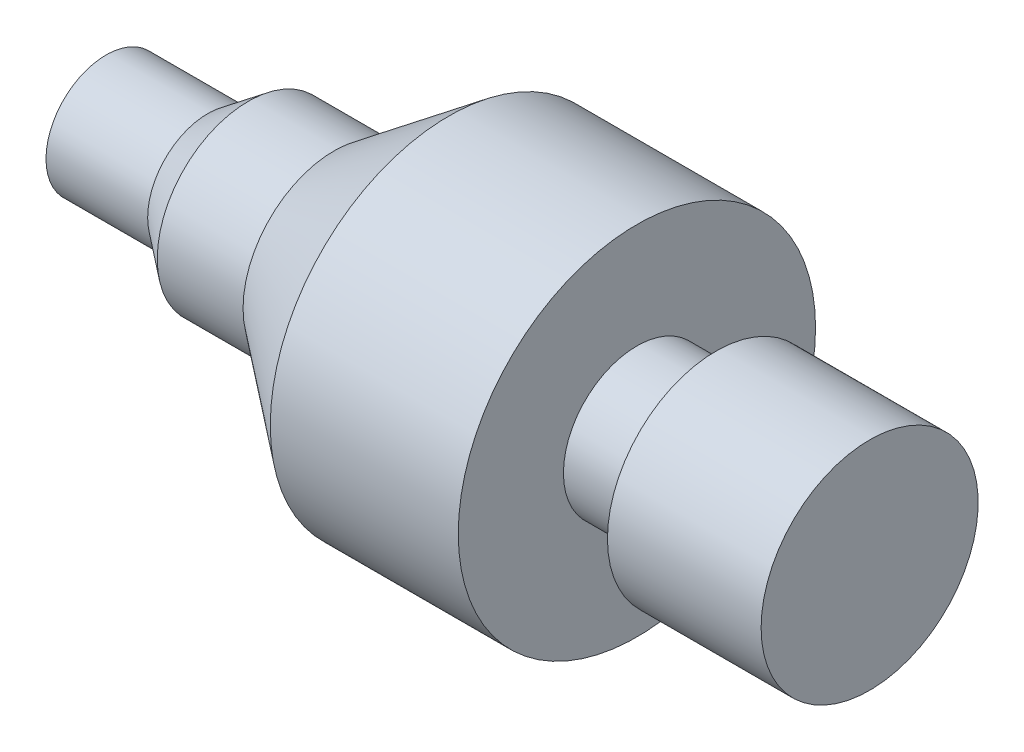
SolidWorks part; units mm, degrees
material "Nickel"
ref_plane "Front Plane" through (0, 0, 0) normal (0, 0, 1) x (1, 0, 0)
ref_plane "Top Plane" through (0, 0, 0) normal (0, 1, 0) x (1, 0, 0)
ref_plane "Right Plane" through (0, 0, 0) normal (1, 0, 0) x (0, 0, -1)
sketch "Sketch1" plane through (0, 0, 0) normal (0, 0, 1) x (1, 0, 0)
  circle A0 centre (-1.4989, 0) radius 34.7002
sketch "Sketch2" plane through (0, 0, 0) normal (0, 0, 1) x (1, 0, 0)
  line L0 (0, 0) -> (68.4973, 0) construction
  line L1 (68.4973, 0) -> (68.4973, 9.7366)
  line L2 (68.4973, 9.7366) -> (54.7122, 9.7366)
  line L3 (54.7122, 9.7366) -> (54.7122, 6.5914)
  line L4 (54.7122, 6.5914) -> (47.6189, 6.5914)
  line L5 (47.6189, 6.5914) -> (47.6189, 16.0269)
  line L6 (47.6189, 16.0269) -> (30.7556, 16.0269)
  line L7 (30.7556, 16.0269) -> (20.4502, 8.164)
  line L8 (20.4502, 8.164) -> (12.7546, 8.164)
  line L9 (12.7546, 8.164) -> (9.1192, 5.3902)
  line L10 (9.1192, 5.3902) -> (0, 5.3902)
  line L11 (0, 5.3902) -> (0, 0)
  line L12 (0, 0) -> (68.4973, 0)
revolve "Revolve1" add sketch "Sketch2" angle 360 about L0
